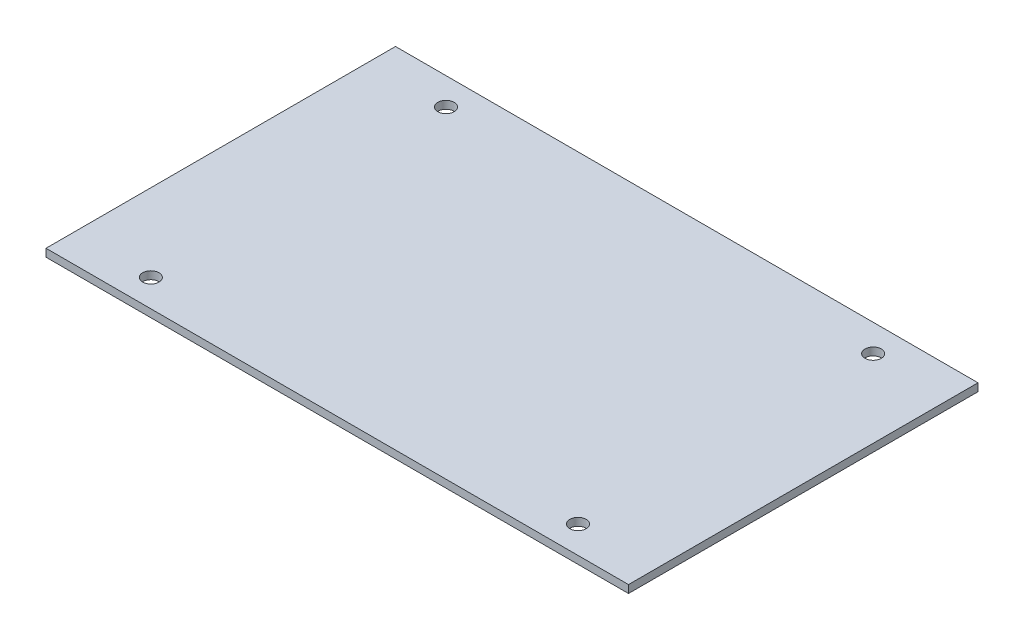
SolidWorks part; units mm, degrees
ref_plane "前视基准面" through (0, 0, 0) normal (0, 0, 1) x (1, 0, 0)
ref_plane "上视基准面" through (0, 0, 0) normal (0, 1, 0) x (1, 0, 0)
ref_plane "右视基准面" through (0, 0, 0) normal (1, 0, 0) x (0, 0, -1)
sketch "草图1" plane through (0, 0, 0) normal (0, 1, 0) x (1, 0, 0)
  line L0 (-75, 0) -> (75, 0) construction
  line L1 (-75, -45) -> (75, -45)
  line L2 (-75, -45) -> (-75, 45)
  line L3 (-75, 45) -> (75, 45)
  line L4 (75, -45) -> (75, 45)
  line L5 (-75, -45) -> (75, 45) construction
  line L6 (-75, 45) -> (75, -45) construction
  line L7 (0, 45) -> (0, -45) construction
  circle A0 centre (-55, 38) radius 2.1
  circle A1 centre (55, 38) radius 2.1
  circle A2 centre (-55, -38) radius 2.1
  circle A3 centre (55, -38) radius 2.1
  point P0 (0, 0)
  dimension "D3" = 4.2
  dimension "D4" = 110
  dimension "D5" = 76
  dimension "D6" = 110
  dimension "D7" = 76
  dimension "D8" = 38
  dimension "D9" = 38
  dimension "D10" = 55
  dimension "D11" = 55
  dimension "D1" = 150
  dimension "D2" = 90
extrude "凸台-拉伸1" add sketch "草图1" along normal blind 2
